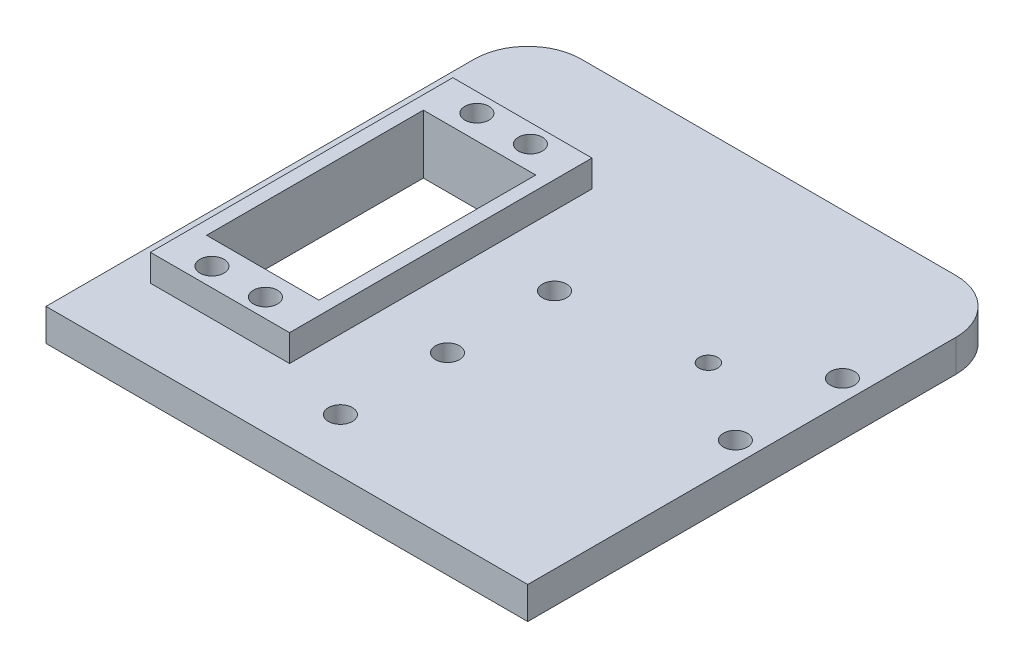
SolidWorks part; units mm, degrees
ref_plane "Front Plane" through (0, 0, 0) normal (0, 0, 1) x (1, 0, 0)
ref_plane "Top Plane" through (0, 0, 0) normal (0, 1, 0) x (1, 0, 0)
ref_plane "Right Plane" through (0, 0, 0) normal (1, 0, 0) x (0, 0, -1)
sketch "Sketch1" plane through (0, 0, 0) normal (0, 1, 0) x (1, 0, 0)
  line L1 (-45, 40) -> (45, 40)
  line L2 (-45, 40) -> (-45, -50)
  line L3 (-45, -50) -> (45, -50)
  line L4 (45, 40) -> (45, -50)
  dimension "D1" = 90
  dimension "D2" = 90
  dimension "D3" = 45
  dimension "D4" = 40
extrude "Boss-Extrude1" add sketch "Sketch1" along normal blind 6
sketch "Sketch2" plane through (0, 6, 0) normal (0, 1, 0) x (1, 0, 0)
  line L0 (45, 40) -> (-45, 40) construction
  line L1 (-39, 20) -> (-13, 20)
  line L2 (-39, 20) -> (-39, -36.5)
  line L3 (-39, -36.5) -> (-13, -36.5)
  line L4 (-13, 20) -> (-13, -36.5)
  line L5 (-45, 40) -> (-45, -50) construction
  dimension "D1" = 26
  dimension "D2" = 56.5
  dimension "D3" = 20
  dimension "D4" = 6
extrude "Boss-Extrude2" add sketch "Sketch2" along normal blind 5
sketch "Sketch3" plane through (0, 11, 0) normal (0, 1, 0) x (1, 0, 0)
  line L0 (-13, 20) -> (-39, 20) construction
  line L1 (-36.5, 12) -> (-15.5, 12)
  line L2 (-36.5, 12) -> (-36.5, -28.5)
  line L3 (-36.5, -28.5) -> (-15.5, -28.5)
  line L4 (-15.5, 12) -> (-15.5, -28.5)
  line L6 (-39, 20) -> (-39, -36.5) construction
  dimension "D1" = 21
  dimension "D2" = 40.5
  dimension "D3" = 8
  dimension "D4" = 2.5
extrude "Cut-Extrude1" cut sketch "Sketch3" against normal blind 12
sketch "Sketch4" plane through (0, 11, 0) normal (0, 1, 0) x (1, 0, 0)
  line L0 (-15.5, 12) -> (-36.5, 12) construction
  line L1 (-36.5, -28.5) -> (-15.5, -28.5) construction
  line L2 (-13, -36.5) -> (-13, 20) construction
  circle A0 centre (-31, 16.5) radius 2.25
  circle A1 centre (-21, 16.5) radius 2.25
  circle A2 centre (-31, -33) radius 2.25
  circle A3 centre (-21, -33) radius 2.25
  point P8 (0, 0)
  dimension "D1" = 4.5
  dimension "D2" = 4.5
  dimension "D3" = 10
  dimension "D4" = 10
  dimension "D5" = 4.5
  dimension "D6" = 4.5
  dimension "D7" = 4.5
  dimension "D8" = 4.5
  dimension "D9" = 8
  dimension "D10" = 8
  dimension "D11" = 4.5
  dimension "D12" = 4.5
extrude "Cut-Extrude2" cut sketch "Sketch4" against normal blind 10
sketch "Sketch5" plane through (0, 6, 0) normal (0, 1, 0) x (1, 0, 0)
  line L0 (-15.5, 12) -> (-36.5, 12) construction
  line L1 (-15.5, -28.5) -> (-15.5, 12) construction
  line L6 (-45, 40) -> (-45, -50) construction
  line L7 (-39, 20) -> (-39, -36.5) construction
  circle A0 centre (26, 2.75) radius 1.75
  dimension "D1" = 3.5
  dimension "D2" = 9.25
  dimension "D3" = 41.5
  dimension "D4" = 6
extrude "Cut-Extrude3" cut sketch "Sketch5" against normal blind 11
fillet "Fillet1" radius 10 1 edges at (-45, 3, -40)
fillet "Fillet2" radius 10 1 edges at (45, 3, -40)
sketch "Sketch6" plane through (0, 0, 0) normal (0, -1, 0) x (-1, 0, 0)
  circle A0 centre (-41.042, 12.75) radius 2.25
  circle A1 centre (41.6974, 12.75) radius 2.25
  circle A2 centre (-41.042, -7.25) radius 2.25
  circle A3 centre (41.6974, -7.25) radius 2.25
  circle A4 centre (-26, 2.75) radius 1.75 construction
  dimension "D1" = 4.5
  dimension "D2" = 4.5
  dimension "D3" = 4.5
  dimension "D4" = 4.5
  dimension "D5" = 10
  dimension "D6" = 10
  dimension "D7" = 10
  dimension "D8" = 10
extrude "Cut-Extrude4" cut sketch "Sketch6" against normal blind 11
sketch "Sketch7" plane through (0, 0, 0) normal (0, -1, 0) x (-1, 0, 0)
  circle A0 centre (-26, 2.75) radius 7.5
  circle A1 centre (-26, 2.75) radius 9.5
  dimension "D1" = 15
  dimension "D2" = 19
extrude "Boss-Extrude3" add sketch "Sketch7" along normal blind 2
sketch "Sketch8" plane through (0, 6, 0) normal (0, 1, 0) x (1, 0, 0)
  circle A0 centre (0, 0) radius 2.25
  circle A1 centre (0, -20) radius 2.25
  circle A2 centre (0, -40) radius 2.25
  dimension "D1" = 4.5
  dimension "D2" = 4.5
  dimension "D3" = 4.5
  dimension "D4" = 20
  dimension "D5" = 20
extrude "Cut-Extrude5" cut sketch "Sketch8" against normal blind 10
